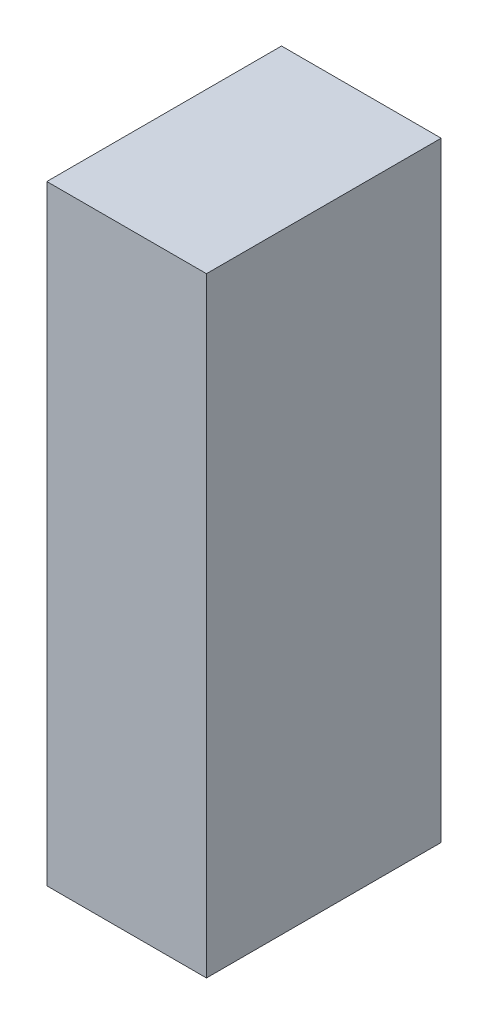
SolidWorks part; units mm, degrees
ref_plane "Front Plane" through (0, 0, 0) normal (0, 0, 1) x (1, 0, 0)
ref_plane "Top Plane" through (0, 0, 0) normal (0, 1, 0) x (1, 0, 0)
ref_plane "Right Plane" through (0, 0, 0) normal (1, 0, 0) x (0, 0, -1)
sketch "Sketch2" plane through (0, 0, 0) normal (0, 1, 0) x (1, 0, 0)
  line L1 (0, 0) -> (11.7, 0)
  line L2 (0, 0) -> (0, 17.2)
  line L3 (0, 17.2) -> (11.7, 17.2)
  line L4 (11.7, 0) -> (11.7, 17.2)
  dimension "D1" = 11.7
  dimension "D2" = 17.2
extrude "Boss-Extrude1" add sketch "Sketch2" along normal blind 44.7
